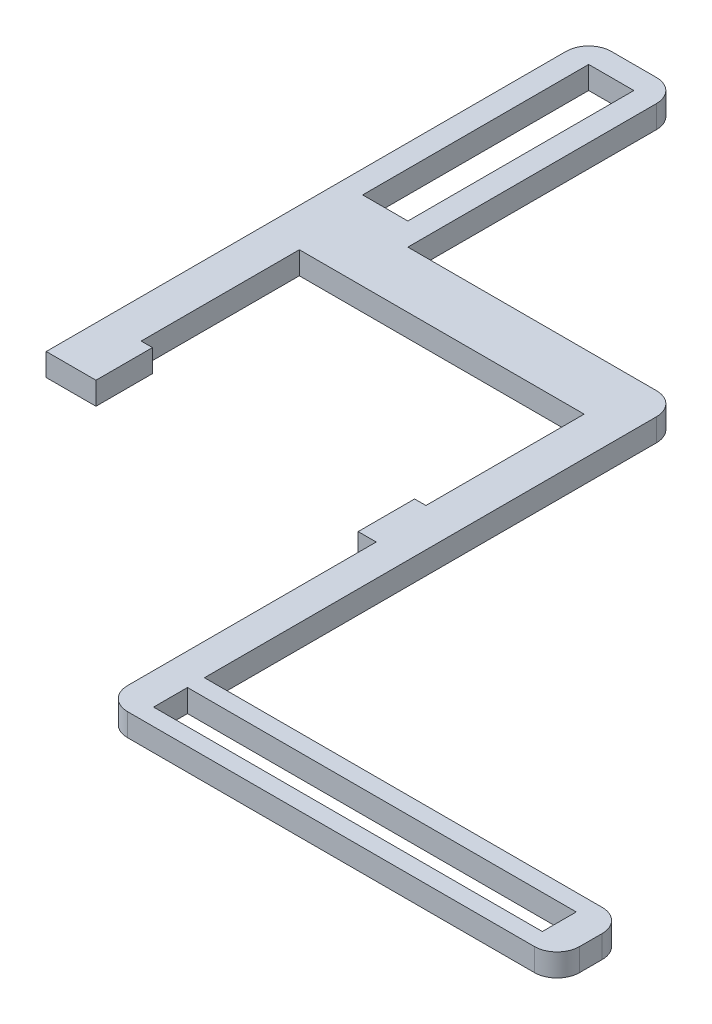
SolidWorks part; units mm, degrees
ref_plane "Front Plane" through (0, 0, 0) normal (0, 0, 1) x (1, 0, 0)
ref_plane "Top Plane" through (0, 0, 0) normal (0, 1, 0) x (1, 0, 0)
ref_plane "Right Plane" through (0, 0, 0) normal (1, 0, 0) x (0, 0, -1)
sketch "Sketch1" plane through (0, 0, 0) normal (0, 1, 0) x (1, 0, 0)
  line L0 (0, -17.5) -> (0, -30) construction
  line L1 (-31.5, -17.5) -> (31.5, -17.5)
  line L2 (-31.5, -17.5) -> (-31.5, 17.5)
  line L3 (-31.5, 17.5) -> (31.5, 17.5)
  line L4 (31.5, -17.5) -> (31.5, 17.5)
  line L5 (-31.5, -17.5) -> (31.5, 17.5) construction
  line L6 (-31.5, 17.5) -> (31.5, -17.5) construction
  line L7 (-40, -30) -> (40, -30)
  line L8 (-40, -30) -> (-40, 30)
  line L9 (-40, 30) -> (40, 30)
  line L10 (40, -30) -> (40, 30)
  line L11 (-40, -30) -> (40, 30) construction
  line L12 (-40, 30) -> (40, -30) construction
  line L13 (40, -30) -> (33, -30)
  line L14 (40, -30) -> (40, -75)
  line L15 (40, -75) -> (33, -75)
  line L16 (33, -30) -> (33, -75)
  line L17 (33, -75) -> (133, -75)
  line L18 (33, -75) -> (33, -90)
  line L19 (33, -90) -> (133, -90)
  line L20 (133, -75) -> (133, -90)
  line L21 (-40, 30) -> (-20, 30)
  line L22 (-40, 30) -> (-40, 90)
  line L23 (-40, 90) -> (-20, 90)
  line L24 (-20, 30) -> (-20, 90)
  line L25 (-29, -17.5) -> (-29, -30)
  line L26 (29, -17.5) -> (29, -30)
  point P0 (0, 0)
  point P6 (0, 0)
  dimension "D1" = 80
  dimension "D2" = 60
  dimension "D3" = 63
  dimension "D4" = 35
  dimension "D5" = 7
  dimension "D6" = 45
  dimension "D7" = 15
  dimension "D8" = 100
  dimension "D9" = 20
  dimension "D10" = 60
  dimension "D11" = 58
extrude "Boss-Extrude1" add sketch "Sketch1" along normal blind 5 contours L9 L24 L23 L22 | L7 L10 L9 L8 L4 L1 L2 L3 | L7 L16 L15 L14 | L17 L20 L19 L18
fillet "Fillet2" radius 5 6 edges at (133, 2.5, 90) (133, 2.5, 75) (33, 2.5, 90) (-20, 2.5, -90) (-40, 2.5, -90) (40, 2.5, -30)
sketch "Sketch2" plane through (0, 5, 0) normal (0, 1, 0) x (1, 0, 0)
  line L0 (83, -90) -> (83, -75) construction
  line L1 (38, -90) -> (128, -90) construction
  line L2 (40, -75) -> (128, -75) construction
  line L3 (40, -75) -> (40, 25) construction
  line L4 (40, -86.25) -> (126, -86.25)
  line L5 (40, -86.25) -> (40, -78.75)
  line L6 (40, -78.75) -> (126, -78.75)
  line L7 (126, -86.25) -> (126, -78.75)
  line L8 (40, -86.25) -> (126, -78.75) construction
  line L9 (40, -78.75) -> (126, -86.25) construction
  line L10 (-30, 90) -> (-30, 30) construction
  line L11 (-35, 90) -> (-25, 90) construction
  line L12 (-20, 30) -> (-40, 30) construction
  line L13 (-40, -30) -> (-40, 85) construction
  line L15 (-35, 35) -> (-25, 35)
  line L16 (-35, 35) -> (-35, 85)
  line L17 (-35, 85) -> (-25, 85)
  line L18 (-25, 35) -> (-25, 85)
  line L19 (-35, 35) -> (-25, 85) construction
  line L20 (-35, 85) -> (-25, 35) construction
  point P6 (83, -82.5)
  point P17 (-30, 60)
  dimension "D1" = 7.5
  dimension "D2" = 50
  dimension "D3" = 10
extrude "Cut-Extrude1" cut sketch "Sketch2" against normal through all
